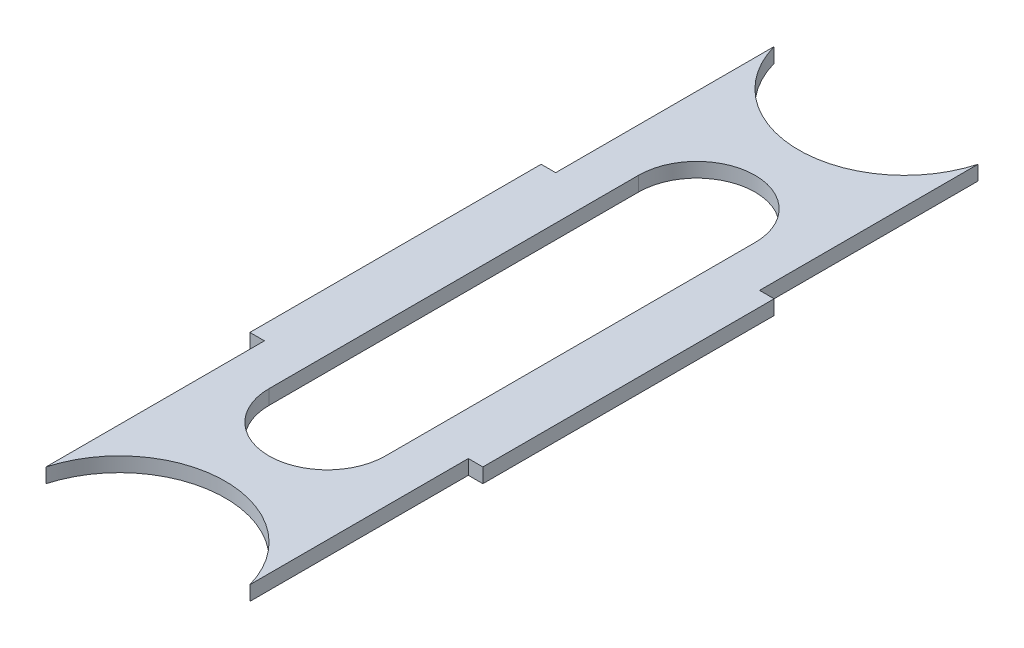
SolidWorks part; units mm, degrees
material "AISI 4130 Steel, annealed at 865C"
ref_plane "X-Y Datum" through (0, 0, 0) normal (0, 0, 1) x (1, 0, 0)
ref_plane "X-Z Datum" through (0, 0, 0) normal (0, 1, 0) x (1, 0, 0)
ref_plane "Y-Z Datum" through (0, 0, 0) normal (1, 0, 0) x (0, 0, -1)
sketch "Sketch1" plane through (0, 0, 0) normal (0, 1, 0) x (1, 0, 0)
  line L0 (11.1125, -15.875) -> (12.7, -15.875)
  line L1 (11.1125, 39.6875) -> (-11.1125, 39.6875) construction
  line L2 (11.1125, 39.6875) -> (11.1125, -39.6875)
  line L3 (11.1125, -39.6875) -> (-11.1125, -39.6875) construction
  line L4 (-11.1125, 39.6875) -> (-11.1125, -39.6875)
  line L5 (11.1125, 39.6875) -> (-11.1125, -39.6875) construction
  line L6 (11.1125, -39.6875) -> (-11.1125, 39.6875) construction
  line L7 (12.7, -15.875) -> (12.7, 15.875)
  line L8 (12.7, 15.875) -> (11.1125, 15.875)
  line L9 (0, -55) -> (0, 55) construction
  line L10 (-12.7, -15.875) -> (-12.7, 15.875)
  line L11 (-12.7, 15.875) -> (-11.1125, 15.875)
  line L12 (-11.1125, -15.875) -> (-12.7, -15.875)
  line L13 (0, 20.1466) -> (0, -20.1466) construction
  line L18 (6.35, 20.1466) -> (6.35, -20.1466)
  line L19 (-6.35, 20.1466) -> (-6.35, -20.1466)
  line L20 (0, -31.2591) -> (0, -26.4966) construction
  line L21 (6.35, 0) -> (11.1125, 0) construction
  arc A1 (11.1125, -39.6875) -> (-11.1125, -39.6875) centre (0, -42.799) ccw
  arc A2 (-11.1125, 39.6875) -> (11.1125, 39.6875) centre (0, 42.799) ccw
  arc A3 (6.35, 20.1466) -> (-6.35, 20.1466) centre (0, 20.1466) ccw
  arc A4 (-6.35, -20.1466) -> (6.35, -20.1466) centre (0, -20.1466) ccw
  point P0 (0, 0)
  point P12 (12.7, 0)
  point P19 (0, 0)
  point P22 (0, 0)
  dimension "D1" = 1.5875
  dimension "D2" = 31.75
  dimension "D3" = 22.225
  dimension "D4" = 79.375
  dimension "D5" = 4.7625
extrude "Boss-Extrude1" add sketch "Sketch1" along normal blind 1.5875
